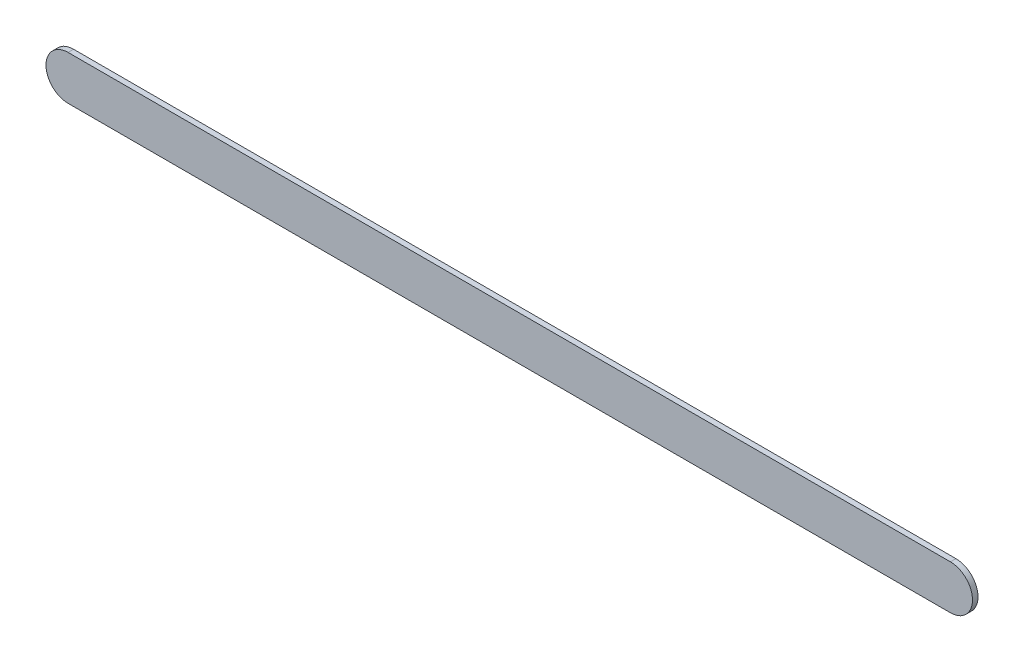
SolidWorks part; units mm, degrees
material "Plain Carbon Steel"
ref_plane "Front Plane" through (0, 0, 0) normal (0, 0, 1) x (1, 0, 0)
ref_plane "Top Plane" through (0, 0, 0) normal (0, 1, 0) x (1, 0, 0)
ref_plane "Right Plane" through (0, 0, 0) normal (1, 0, 0) x (0, 0, -1)
sketch "Sketch1" plane through (0, 0, 0) normal (0, 0, 1) x (1, 0, 0)
  line L0 (508, 0) -> (-508, 0) construction
  line L1 (3.4925, 0) -> (-3.4925, 0) construction
  line L2 (508, -25.4) -> (-508, -25.4)
  line L3 (508, 25.4) -> (-508, 25.4)
  arc A0 (508, -25.4) -> (508, 25.4) centre (508, 0) ccw
  arc A1 (-508, 25.4) -> (-508, -25.4) centre (-508, 0) ccw
  point P5 (0, 0)
  dimension "D1" = 50.8
  dimension "D2" = 1066.8
extrude "Boss-Extrude1" add sketch "Sketch1" along normal mid plane 6.35
